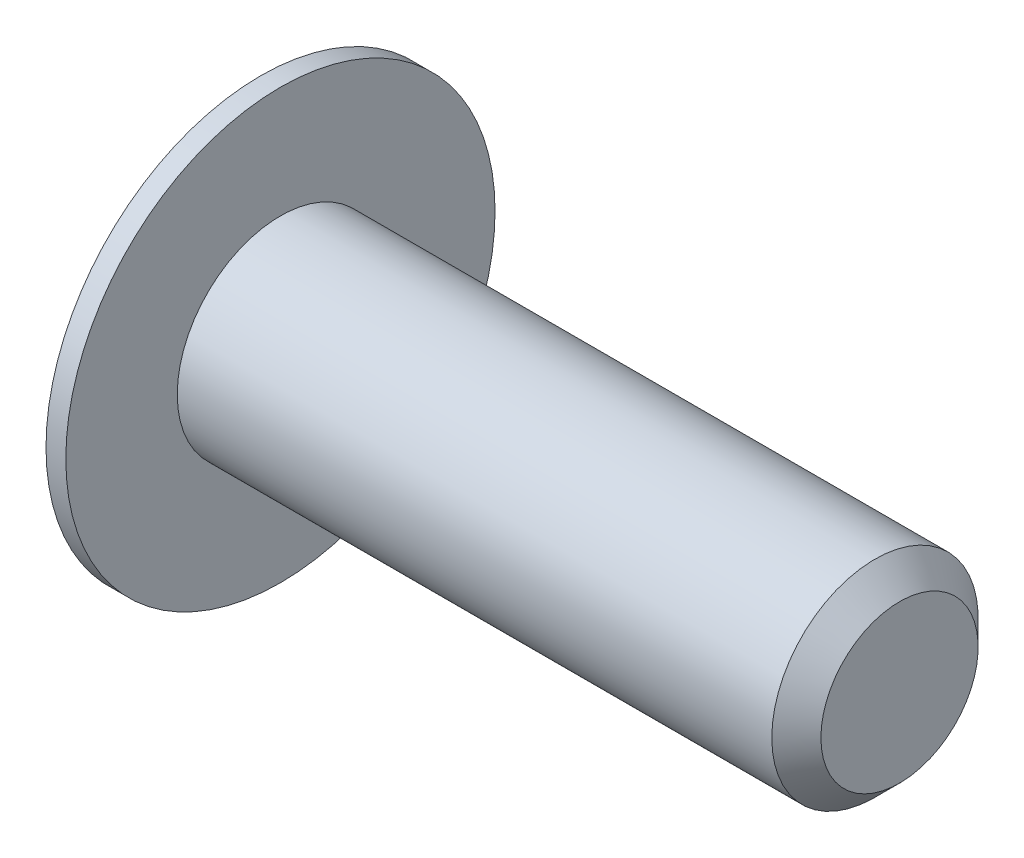
SolidWorks part; units mm, degrees
ref_plane "Front Plane" through (0, 0, 0) normal (0, 0, 1) x (1, 0, 0)
ref_plane "Top Plane" through (0, 0, 0) normal (0, 1, 0) x (1, 0, 0)
ref_plane "Right Plane" through (0, 0, 0) normal (1, 0, 0) x (0, 0, -1)
ref_plane "Plane1" through (0, 0, 0) normal (0, 0, -1) x (-1, 0, 0)
sketch "Sketch1" plane through (0, 0, 0) normal (0, 0, -1) x (-1, 0, 0)
  line L0 (0, 6.604) -> (0, 0)
  line L1 (0, 0) -> (3.048, 0)
  line L2 (3.048, 0) -> (3.048, 2.4384)
  line L3 (0.6096, 5.9436) -> (0.6096, 6.604)
  line L4 (0.6096, 6.604) -> (0, 6.604)
  line L5 (0, 0) -> (3.048, 0) construction
  spline S0 degree 3 poles (0.6096, 5.9436) (1.7565, 5.1007) (2.6566, 3.8068) (3.048, 2.4384) knots 0 0 0 0 1 1 1 1
revolve "Revolve1" add sketch "Sketch1" angle 360 about L5
sketch "Sketch2" plane through (0, 0, 0) normal (1, 0, 0) x (0, 0, -1)
  circle A0 centre (0, 0) radius 3.175
extrude "Boss-Extrude1" add sketch "Sketch2" along normal blind 19.05
sketch "Sketch3" plane through (-3.048, 0, 0) normal (-1, 0, 0) x (0, 0, 1)
  line L0 (0, -2.3464) -> (2.032, -1.1732)
  line L1 (2.032, -1.1732) -> (2.032, 1.1732)
  line L2 (2.032, 1.1732) -> (0, 2.3464)
  line L3 (0, 2.3464) -> (-2.032, 1.1732)
  line L4 (-2.032, 1.1732) -> (-2.032, -1.1732)
  line L5 (-2.032, -1.1732) -> (0, -2.3464)
extrude "Cut-Extrude1" cut sketch "Sketch3" against normal blind 2.286
chamfer "Chamfer1" distance 0.7556 angle 45 1 edges at (19.05, 0, -3.175)
